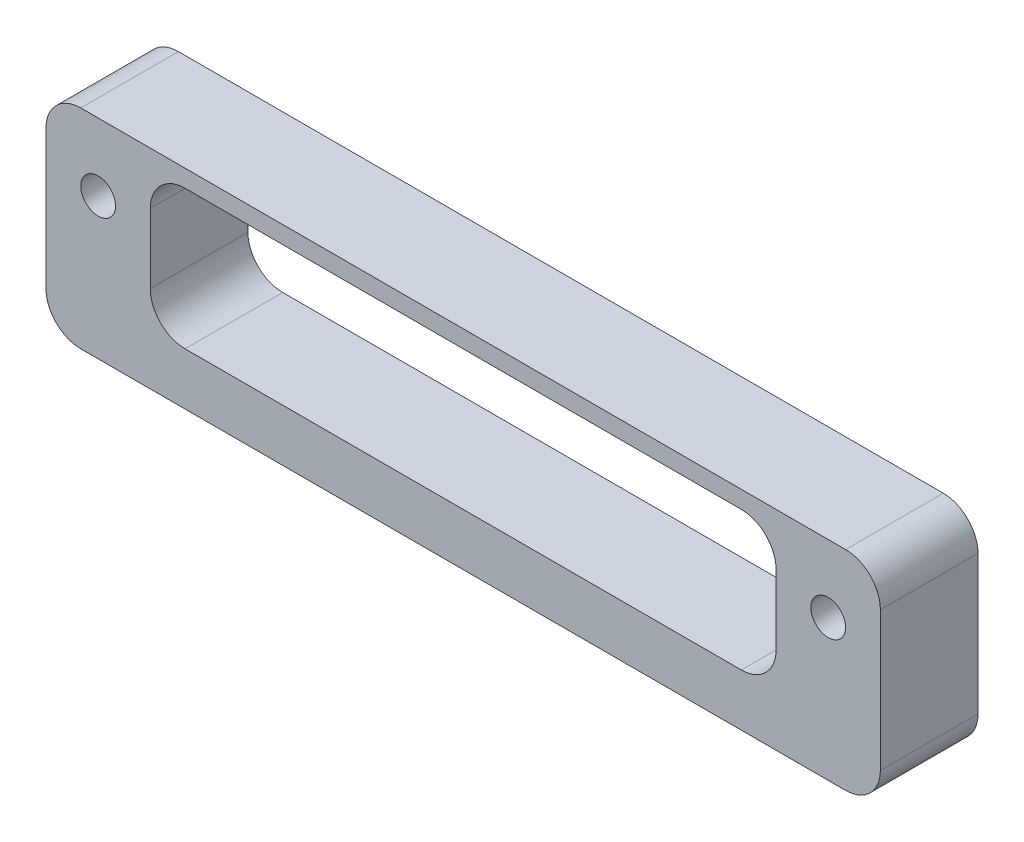
SolidWorks part; units mm, degrees
ref_plane "Front Plane" through (0, 0, 0) normal (0, 0, 1) x (1, 0, 0)
ref_plane "Top Plane" through (0, 0, 0) normal (0, 1, 0) x (1, 0, 0)
ref_plane "Right Plane" through (0, 0, 0) normal (1, 0, 0) x (0, 0, -1)
sketch "Sketch1" plane through (0, 0, 0) normal (0, 0, 1) x (1, 0, 0)
  line L1 (76.2, -19.05) -> (-76.2, -19.05)
  line L2 (76.2, -19.05) -> (76.2, 19.05)
  line L3 (76.2, 19.05) -> (-76.2, 19.05)
  line L4 (-76.2, -19.05) -> (-76.2, 19.05)
  line L5 (76.2, -19.05) -> (-76.2, 19.05) construction
  line L6 (76.2, 19.05) -> (-76.2, -19.05) construction
  point P0 (0, 0)
  dimension "D1" = 38.1
  dimension "D2" = 152.4
extrude "Boss-Extrude1" add sketch "Sketch1" along normal blind 17.8308
sketch "Sketch2" plane through (0, 0, 17.8308) normal (0, 0, 1) x (1, 0, 0)
  line L0 (-76.2, -19.05) -> (76.2, -19.05) construction
  line L1 (-57.15, 15.875) -> (57.15, 15.875)
  line L2 (-57.15, 15.875) -> (-57.15, -9.525)
  line L3 (-57.15, -9.525) -> (57.15, -9.525)
  line L4 (57.15, 15.875) -> (57.15, -9.525)
  point P4 (0, -9.525)
  point P7 (0, -19.05)
  dimension "D1" = 25.4
  dimension "D2" = 114.3
  dimension "D3" = 0
  dimension "D4" = 9.525
extrude "Cut-Extrude1" cut sketch "Sketch2" against normal through all
fillet "Fillet1" radius 6.35 8 edges at (-76.2, -19.05, 8.9154) (-76.2, 19.05, 8.9154) (-57.15, -9.525, 8.9154) (57.15, -9.525, 8.9154) (76.2, -19.05, 8.9154) (76.2, 19.05, 8.9154) (57.15, 15.875, 8.9154) (-57.15, 15.875, 8.9154)
sketch "Sketch3" plane through (0, 0, 17.8308) normal (0, 0, 1) x (1, 0, 0)
  line L0 (-57.15, 22.588) -> (-57.15, -9.162) construction
  line L1 (-76.2, 12.7) -> (-76.2, -12.7) construction
  line L2 (57.15, 22.588) -> (57.15, -9.162) construction
  line L3 (76.2, -12.7) -> (76.2, 12.7) construction
  circle A0 centre (-66.675, 6.713) radius 3.175
  circle A1 centre (66.675, 6.713) radius 3.175
  point P4 (-57.15, 6.713)
  point P11 (57.15, 6.713)
  dimension "D1" = 6.35
  dimension "D4" = 6.35
  dimension "D2" = 0
  dimension "D3" = 9.525
  dimension "D5" = 0
  dimension "D6" = 9.525
extrude "Cut-Extrude2" cut sketch "Sketch3" against normal through all
